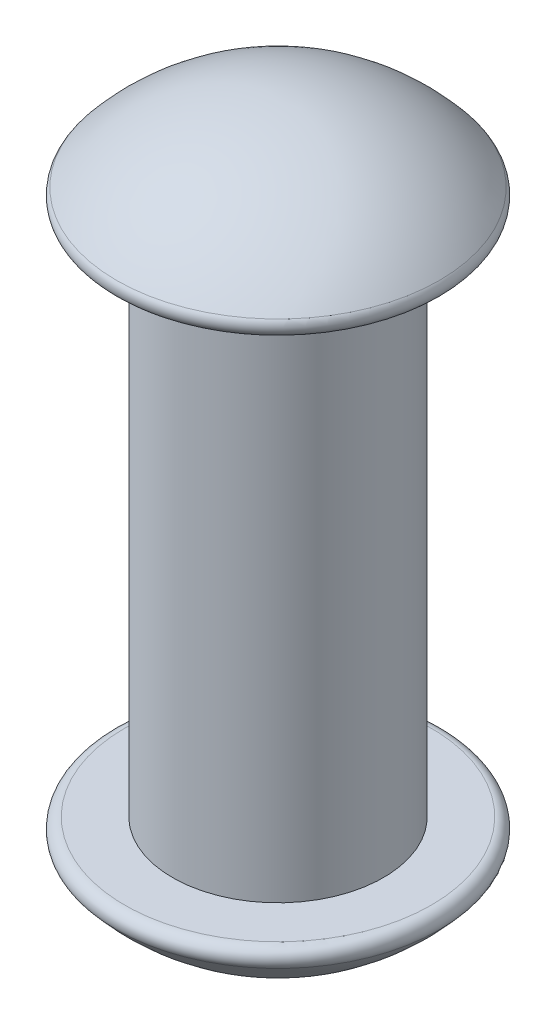
SolidWorks part; units mm, degrees
ref_plane "Front Plane" through (0, 0, 0) normal (0, 0, 1) x (1, 0, 0)
ref_plane "Top Plane" through (0, 0, 0) normal (0, 1, 0) x (1, 0, 0)
ref_plane "Right Plane" through (0, 0, 0) normal (1, 0, 0) x (0, 0, -1)
sketch "Sketch1" plane through (0, 0, 0) normal (0, 0, 1) x (1, 0, 0)
  line L0 (0, 0) -> (2, 0)
  line L1 (2, 0) -> (2, 5)
  line L2 (2, 5) -> (3.3072, 5)
  line L3 (0, 6.75) -> (0, 0)
  arc A1 (0, 6.75) -> (3.3072, 5) centre (0, 2.75) cw
  point P7 (0, 2.7502)
  dimension "D4" = 4
  dimension "D1" = 1.75
  dimension "D2" = 5
  dimension "D3" = 2
revolve "Revolve1" add sketch "Sketch1" angle 360 about L3
mirror "Mirror1" about plane through (0, 0, 0) normal (0, 1, 0) of "Revolve1"
fillet "Fillet1" radius 0.2 2 edges at (-3.3072, 5, 0) (-3.3072, -5, 0)
